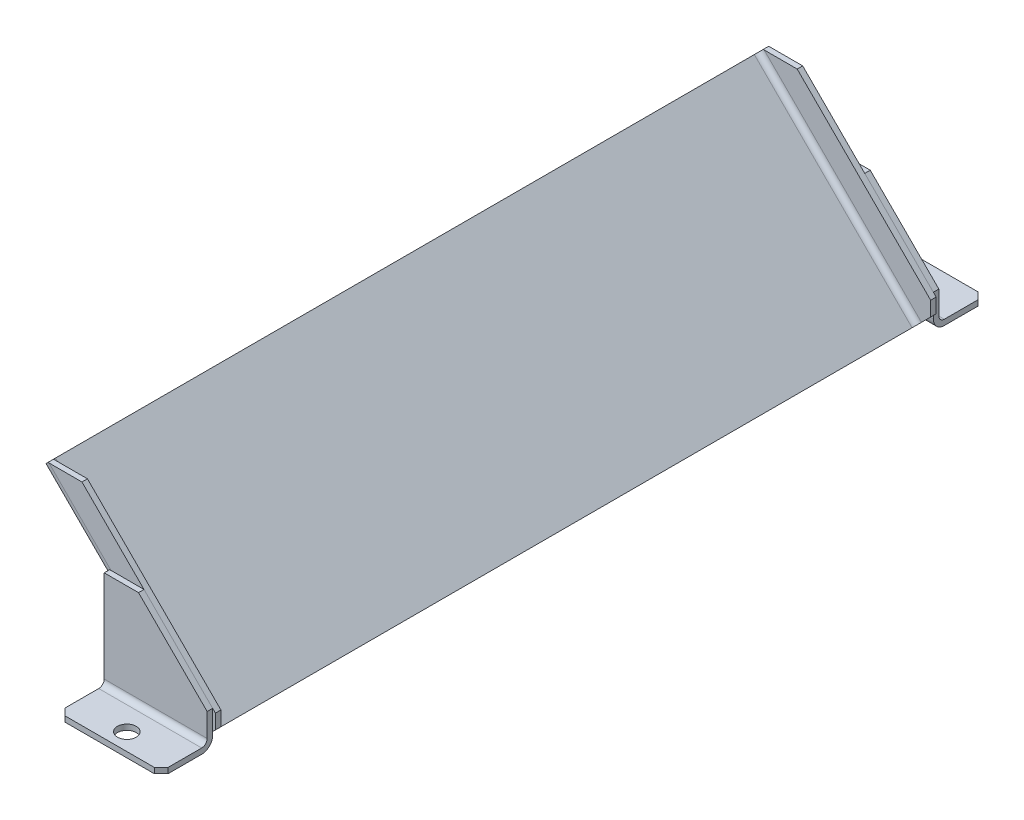
SolidWorks part; units mm, degrees
ref_plane "Front" through (0, 0, 0) normal (0, 0, 1) x (1, 0, 0)
ref_plane "Top" through (0, 0, 0) normal (0, 1, 0) x (1, 0, 0)
ref_plane "Right" through (0, 0, 0) normal (1, 0, 0) x (0, 0, -1)
sketch "Sketch1" plane through (0, 0, 0) normal (1, 0, 0) x (0, 0, -1)
  line L0 (0, 69.9751) -> (0, -17.0753) construction
  line L1 (-120, 0) -> (-105, 0)
  line L2 (-105, 0) -> (-105, 30)
  line L3 (-105, 30) -> (-106.6, 30)
  line L4 (-106.6, 30) -> (-106.6, 1.6)
  line L5 (-106.6, 1.6) -> (-120, 1.6)
  line L6 (-120, 1.6) -> (-120, 0)
  dimension "D1" = 1.6
  dimension "D2" = 1.6
  dimension "D3" = 15
  dimension "D4" = 30
  dimension "D5" = 105
extrude "Boss-Extrude1" add sketch "Sketch1" along normal blind 30
fillet "Fillet1" radius 1.6 1 edges at (15, 1.6, 106.6)
fillet "Fillet2" radius 3.2 1 edges at (15, 0, 105)
sketch "Sketch2" plane through (0, 0, 0) normal (0, 0, 1) x (1, 0, 0)
  line L0 (10, 30) -> (33, 7)
  line L1 (33, 7) -> (33, 33)
  line L2 (33, 33) -> (10, 33)
  line L3 (10, 30) -> (10, 33)
  line L5 (0, 30) -> (0, 3.2) construction
  line L7 (30, 30) -> (30, 3.2) construction
  dimension "D1" = 45
  dimension "D2" = 10
  dimension "D3" = 30
  dimension "D4" = 3
  dimension "D5" = 3
extrude "Cut-Extrude1" cut sketch "Sketch2" along normal blind 120
chamfer "Chamfer1" distance 2 angle 45 2 edges at (30, 0.8, 120) (0, 0.8, 120)
sketch "Sketch3" plane through (0, 0, 0) normal (0, 0, 1) x (1, 0, 0)
  line L0 (-20.1041, 45.9619) -> (25.8579, 0)
  line L1 (25.8579, 0) -> (32.9289, 7.0711)
  line L2 (32.9289, 7.0711) -> (-13.033, 53.033)
  line L3 (-13.033, 53.033) -> (-20.1041, 45.9619)
  line L5 (10, 30) -> (30, 10) construction
  line L8 (28, 0) -> (2, 0) construction
  dimension "D1" = 10
  dimension "D2" = 10
  dimension "D4" = 65
extrude "Cut-Extrude2" add sketch "Sketch3" along normal mid plane 210 separate body
shell "Shell1" thickness 1.6
fillet "Fillet3" radius 1.6 2 edges at (4.0083, 24.1123, 103.4) (4.0083, 24.1123, -103.4)
fillet "Fillet4" radius 3.2 2 edges at (2.8769, 22.981, 105) (2.8769, 22.981, -105)
mirror "MirrorSolid1" about plane through (0, 0, 0) normal (0, 0, 1) of bodies 102
chamfer "Chamfer2" distance 7 angle 45 2 edges at (-13.033, 53.033, -104.2) (-13.033, 53.033, 104.2)
chamfer "Chamfer3" distance 3 angle 45 2 edges at (32.9289, 7.0711, -104.2) (32.9289, 7.0711, 104.2)
hole_wizard "M5 Clearance Hole1" positions "Sketch4" profile "Sketch5" hole size "M5" standard "JIS" end condition through all
sketch "Sketch4" plane through (0, 1.6, 0) normal (0, 1, 0) x (-1, 0, 0)
  line L0 (-81.5802, 0) -> (68.3954, 0) construction
  line L2 (-30, 108.2) -> (-30, 118) construction
  point P0 (-15, 115)
  point P1 (-15, -115)
  dimension "D1" = 230
  dimension "D2" = 15
sketch "Sketch5" plane through (15, 1.6, 115) normal (1, 0, 0) x (0, 0, 1)
  line L0 (0, 0) -> (0, 1.6)
  line L1 (0, 1.6) -> (2.75, 1.6)
  line L2 (2.75, 1.6) -> (2.75, 0)
  line L5 (2.75, 0) -> (0, 0)
  line L11 (0, -6.35) -> (0, 107.95) construction
  dimension "通し穴の直径" = 5.5
  dimension "通し穴の深さ" = 1.6
